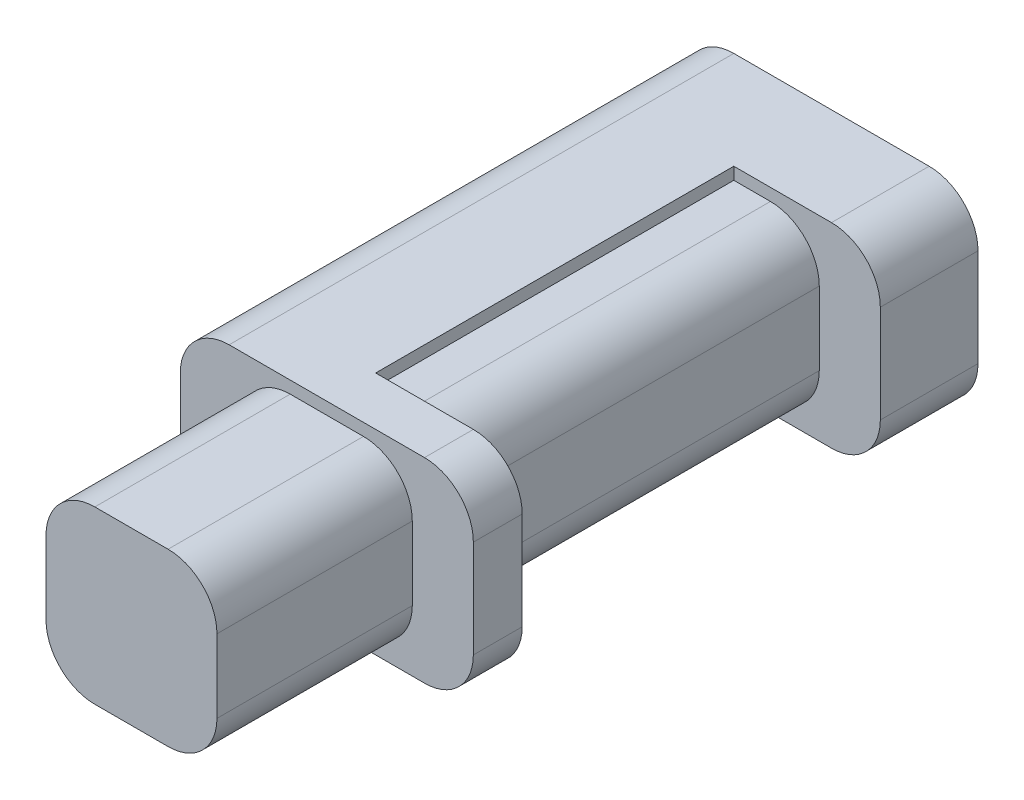
SolidWorks part; units mm, degrees
ref_plane "Front Plane" through (0, 0, 0) normal (0, 0, 1) x (1, 0, 0)
ref_plane "Top Plane" through (0, 0, 0) normal (0, 1, 0) x (1, 0, 0)
ref_plane "Right Plane" through (0, 0, 0) normal (1, 0, 0) x (0, 0, -1)
sketch "Sketch1" plane through (0, 0, 0) normal (0, 0, 1) x (1, 0, 0)
  line L0 (-2.25, 5.25) -> (2.25, 5.25)
  line L1 (5.25, 2.25) -> (5.25, -2.25)
  line L2 (2.25, -5.25) -> (-2.25, -5.25)
  line L3 (-5.25, -2.25) -> (-5.25, 2.25)
  line L4 (0, 5.25) -> (0, -5.25) construction
  line L5 (-5.25, 0) -> (5.25, 0) construction
  arc A0 (2.25, 5.25) -> (5.25, 2.25) centre (2.25, 2.25) cw
  arc A1 (5.25, -2.25) -> (2.25, -5.25) centre (2.25, -2.25) cw
  arc A2 (-2.25, -5.25) -> (-5.25, -2.25) centre (-2.25, -2.25) cw
  arc A3 (-5.25, 2.25) -> (-2.25, 5.25) centre (-2.25, 2.25) cw
  dimension "D2" = 3
  dimension "D3" = 3
  dimension "D4" = 3
  dimension "D5" = 3
  dimension "D1" = 4.5
extrude "Boss-Extrude1" add sketch "Sketch1" along normal blind 40
sketch "Sketch2" plane through (0, 0, 0) normal (0, 0, 1) x (1, 0, 0)
  line L16 (0.0004, 6) -> (-0.0004, -6) construction
  line L17 (9, -0.0008) -> (-9, 0.0008) construction
  line L24 (9, -3.0008) -> (9, 2.9992)
  line L25 (-6.0004, -5.9992) -> (5.9996, -6.0008)
  line L26 (-9, 3.0008) -> (-9, -2.9992)
  line L27 (6.0004, 5.9992) -> (-5.9996, 6.0008)
  arc A28 (5.9996, -6.0008) -> (9, -3.0008) centre (6, -3.0008) ccw
  arc A29 (-9, -2.9992) -> (-6.0004, -5.9992) centre (-6, -2.9992) ccw
  arc A30 (-5.9996, 6.0008) -> (-9, 3.0008) centre (-6, 3.0008) ccw
  arc A31 (9, 2.9992) -> (6.0004, 5.9992) centre (6, 2.9992) ccw
  dimension "D3" = 3
  dimension "D1" = 6
  dimension "D2" = 12
extrude "Boss-Extrude2" add sketch "Sketch2" against normal mid plane 6
sketch "Sketch3" plane through (0, 0, 3) normal (0, 0, 1) x (1, 0, 0)
  line L1 (-2.25, -5.25) -> (2.25, -5.25) construction
  line L4 (0.0004, 5.25) -> (-6, 5.25)
  line L5 (-8.2492, 3.0008) -> (-8.2492, -2.9992)
  line L6 (-6.0006, -5.2484) -> (0.0004, -5.25)
  line L7 (2.25, 5.25) -> (-2.25, 5.25) construction
  line L12 (0.0004, 5.25) -> (0.0004, 6)
  line L13 (6.0004, 5.9992) -> (-5.9996, 6.0008) construction
  line L14 (0.0004, -5.25) -> (0.0004, -6)
  line L17 (-6.0004, -5.9992) -> (5.9996, -6.0008) construction
  line L18 (-9, 3.0008) -> (-9, -2.9992) construction
  line L19 (-6.0004, -5.9992) -> (0.0004, -6)
  line L20 (-9, 3.0008) -> (-9, -2.9992)
  line L21 (0.0004, 6) -> (-5.9996, 6.0008)
  arc A1 (-6, 5.25) -> (-8.2492, 3.0008) centre (-6, 3.0008) ccw
  arc A2 (-9, -2.9992) -> (-6.0004, -5.9992) centre (-6, -2.9992) ccw construction
  arc A3 (-5.9996, 6.0008) -> (-9, 3.0008) centre (-6, 3.0008) ccw construction
  arc A4 (-8.2492, -2.9992) -> (-6.0006, -5.2484) centre (-6, -2.9992) ccw
  arc A12 (-9, -2.9992) -> (-6.0004, -5.9992) centre (-6, -2.9992) ccw
  arc A13 (-5.9996, 6.0008) -> (-9, 3.0008) centre (-6, 3.0008) ccw
extrude "Boss-Extrude3" add sketch "Sketch3" along normal blind 25
sketch "Sketch5" plane through (0, 0, 40) normal (0, 0, 1) x (1, 0, 0)
  line L0 (0.0004, -6) -> (5.9996, -6.0008) construction
  line L1 (0.0004, -6) -> (5.9996, -6.0008)
  line L2 (9, -3.0008) -> (9, 2.9992) construction
  line L3 (6.0004, 5.9992) -> (0.0004, 6) construction
  line L12 (-6.0004, -5.9992) -> (0.0004, -6) construction
  line L13 (-9, 3.0008) -> (-9, -2.9992) construction
  line L14 (9, -3.0008) -> (9, 2.9992)
  line L15 (6.0004, 5.9992) -> (0.0004, 6)
  line L16 (-6.0004, -5.9992) -> (0.0004, -6)
  line L17 (-9, 3.0008) -> (-9, -2.9992)
  line L18 (0.0004, 6) -> (-5.9996, 6.0008) construction
  line L19 (0.0004, 6) -> (-5.9996, 6.0008)
  arc A0 (5.9996, -6.0008) -> (9, -3.0008) centre (6, -3.0008) ccw construction
  arc A1 (9, 2.9992) -> (6.0004, 5.9992) centre (6, 2.9992) ccw construction
  arc A2 (-9, -2.9992) -> (-6.0004, -5.9992) centre (-6, -2.9992) ccw construction
  arc A3 (-5.9996, 6.0008) -> (-9, 3.0008) centre (-6, 3.0008) ccw construction
  arc A12 (5.9996, -6.0008) -> (9, -3.0008) centre (6, -3.0008) ccw
  arc A13 (9, 2.9992) -> (6.0004, 5.9992) centre (6, 2.9992) ccw
  arc A14 (-9, -2.9992) -> (-6.0004, -5.9992) centre (-6, -2.9992) ccw
  arc A15 (-5.9996, 6.0008) -> (-9, 3.0008) centre (-6, 3.0008) ccw
extrude "Boss-Extrude4" add sketch "Sketch5" along normal blind 3 from offset 15
